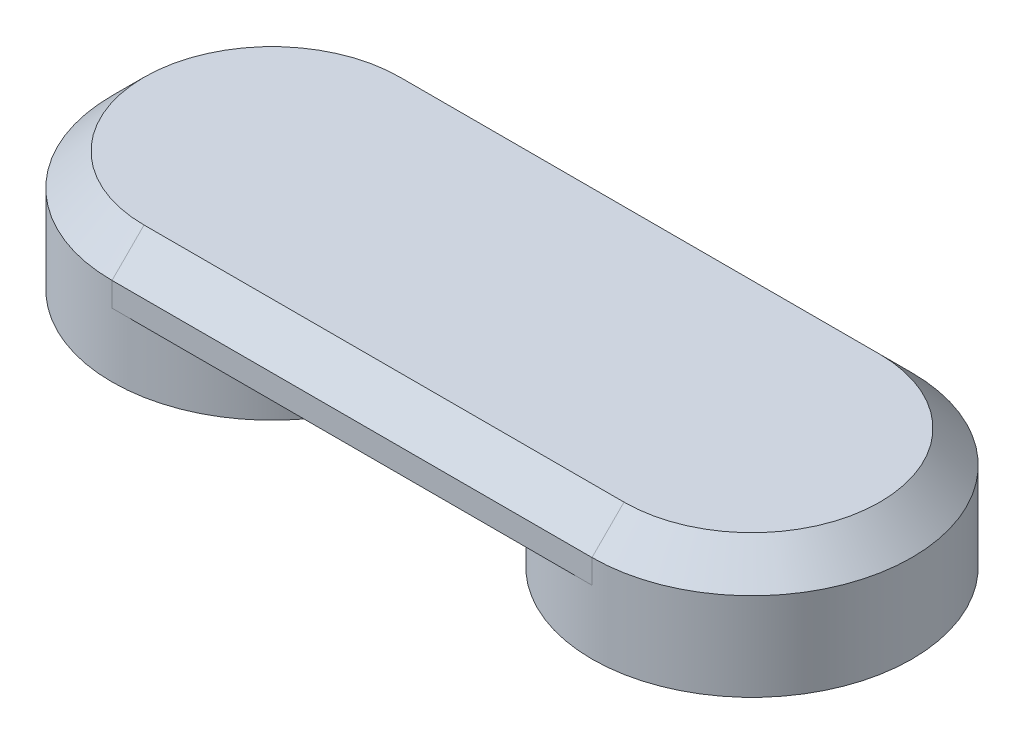
SolidWorks part; units mm, degrees
ref_plane "前视基准面" through (0, 0, 0) normal (0, 0, 1) x (1, 0, 0)
ref_plane "上视基准面" through (0, 0, 0) normal (0, 1, 0) x (1, 0, 0)
ref_plane "右视基准面" through (0, 0, 0) normal (1, 0, 0) x (0, 0, -1)
sketch "草图1" plane through (0, 0, 0) normal (0, 1, 0) x (1, 0, 0)
  line L0 (30, 0) -> (-30, 0) construction
  line L1 (30, -20) -> (-30, -20)
  line L2 (30, 20) -> (-30, 20)
  arc A0 (30, -20) -> (30, 20) centre (30, 0) ccw
  arc A1 (-30, 20) -> (-30, -20) centre (-30, 0) ccw
  point P2 (0, 0)
  dimension "D2" = 20
  dimension "D1" = 60
extrude "凸台-拉伸1" add sketch "草图1" along normal blind 15
chamfer "倒角1" distance 4 angle 45 4 edges at (50, 15, 0) (0, 15, -20) (0, 15, 20) (-50, 15, 0)
sketch "草图3" plane through (0, 0, 0) normal (0, -1, 0) x (1, 0, 0)
  circle A0 centre (-30, 0) radius 20
  circle A1 centre (30, 0) radius 20
  arc A2 (30, -20) -> (30, 20) centre (30, 0) ccw construction
  arc A3 (-30, 20) -> (-30, -20) centre (-30, 0) ccw construction
extrude "切除-拉伸1" cut sketch "草图3" against normal blind 8 flip side to cut
sketch "草图4" plane through (0, 8, 0) normal (0, -1, 0) x (1, 0, 0)
  circle A0 centre (0, 0) radius 5
  dimension "D1" = 10
extrude "凸台-拉伸2" add sketch "草图4" along normal blind 14
